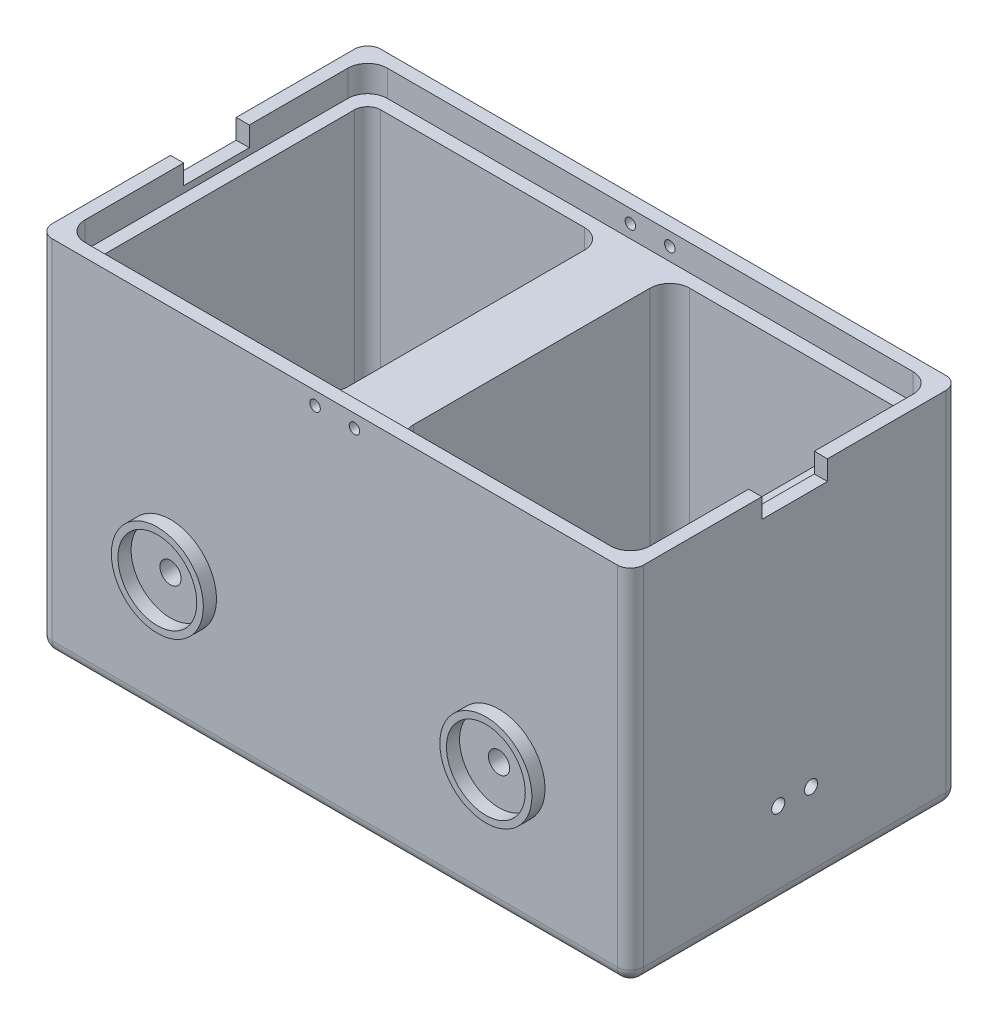
SolidWorks part; units mm, degrees
ref_plane "Front Plane" through (0, 0, 0) normal (0, 0, 1) x (1, 0, 0)
ref_plane "Top Plane" through (0, 0, 0) normal (0, 1, 0) x (1, 0, 0)
ref_plane "Right Plane" through (0, 0, 0) normal (1, 0, 0) x (0, 0, -1)
sketch "Sketch1" plane through (0, 0, 0) normal (0, 1, 0) x (1, 0, 0)
  line L0 (-78.5714, 0) -> (88.7218, 0) construction
  line L1 (-43, 25) -> (43, 25)
  line L2 (-45, 23) -> (-45, -23)
  line L3 (-43, -25) -> (43, -25)
  line L4 (45, 23) -> (45, -23)
  line L5 (0, 21) -> (0, -45.3008) construction
  line L6 (-5, 18) -> (-5, -18)
  line L7 (-39, 21) -> (-8, 21)
  line L8 (-41, 19) -> (-41, -19)
  line L9 (-39, -21) -> (-8, -21)
  line L10 (41, 19) -> (41, -18)
  line L12 (8, 21) -> (39, 21)
  line L13 (8, -21) -> (38, -21)
  line L14 (5, 18) -> (5, -18)
  arc A0 (38, -21) -> (41, -18) centre (38, -18) ccw
  arc A1 (-8, -21) -> (-5, -18) centre (-8, -18) ccw
  arc A2 (8, -21) -> (5, -18) centre (8, -18) cw
  arc A3 (8, 21) -> (5, 18) centre (8, 18) ccw
  arc A4 (-8, 21) -> (-5, 18) centre (-8, 18) cw
  arc A5 (-41, -19) -> (-39, -21) centre (-39, -19) ccw
  arc A6 (-39, 21) -> (-41, 19) centre (-39, 19) ccw
  arc A7 (39, 21) -> (41, 19) centre (39, 19) cw
  arc A8 (43, 25) -> (45, 23) centre (43, 23) cw
  arc A9 (43, -25) -> (45, -23) centre (43, -23) ccw
  arc A10 (-45, -23) -> (-43, -25) centre (-43, -23) ccw
  arc A11 (-43, 25) -> (-45, 23) centre (-43, 23) ccw
  point P21 (2, -21)
  point P24 (1, 21)
  point P37 (45, 25)
  point P40 (45, -25)
  point P45 (-45, 25)
  dimension "D6" = 3
  dimension "D7" = 3
  dimension "D1" = 50
  dimension "D2" = 90
  dimension "D3" = 4
  dimension "D4" = 4
  dimension "D5" = 10
  dimension "D8" = 90
extrude "Boss-Extrude1" add sketch "Sketch1" along normal blind 55
sketch "Sketch2" plane through (0, 0, 0) normal (0, -1, 0) x (1, 0, 0)
  line L0 (45, 23) -> (45, -23) construction
  line L1 (43, -25) -> (-43, -25) construction
  line L2 (-45, -23) -> (-45, 23) construction
  line L3 (-43, 25) -> (43, 25) construction
  line L4 (45, 23) -> (45, -23)
  line L5 (43, -25) -> (-43, -25)
  line L6 (-45, -23) -> (-45, 23)
  line L7 (-43, 25) -> (43, 25)
  arc A0 (-45, -23) -> (-43, -25) centre (-43, -23) ccw construction
  arc A1 (45, 23) -> (43, 25) centre (43, 23) ccw construction
  arc A2 (43, -25) -> (45, -23) centre (43, -23) ccw construction
  arc A3 (-43, 25) -> (-45, 23) centre (-43, 23) ccw construction
  arc A4 (-45, -23) -> (-43, -25) centre (-43, -23) ccw
  arc A5 (45, 23) -> (43, 25) centre (43, 23) ccw
  arc A6 (43, -25) -> (45, -23) centre (43, -23) ccw
  arc A7 (-43, 25) -> (-45, 23) centre (-43, 23) ccw
extrude "Boss-Extrude2" add sketch "Sketch2" against normal blind 4
sketch "Sketch5" plane through (0, 55, 0) normal (0, 1, 0) x (1, 0, 0)
  line L0 (43, 25) -> (-43, 25) construction
  line L1 (-40, 23) -> (40, 23)
  line L2 (-43, 20) -> (-43, -20)
  line L3 (-40, -23) -> (40, -23)
  line L4 (43, 20) -> (43, -20)
  line L5 (-43, -25) -> (43, -25) construction
  line L6 (41, -18) -> (41, 19) construction
  line L7 (-45, 23) -> (-45, -23) construction
  arc A0 (40, 23) -> (43, 20) centre (40, 20) cw
  arc A1 (40, -23) -> (43, -20) centre (40, -20) ccw
  arc A2 (-43, -20) -> (-40, -23) centre (-40, -20) ccw
  arc A3 (-40, 23) -> (-43, 20) centre (-40, 20) ccw
  dimension "D5" = 3
  dimension "D1" = 2
  dimension "D2" = 2
  dimension "D3" = 2
  dimension "D4" = 2
extrude "Cut-Extrude1" cut sketch "Sketch5" against normal blind 4
sketch "Sketch6" plane through (0, 0, 25) normal (0, 0, 1) x (1, 0, 0)
  line L0 (0, 65.631) -> (0, -11.3005) construction
  line L1 (-65.663, 20) -> (62.9075, 20) construction
  line L2 (-25, 33.8045) -> (-25, 8.3012) construction
  line L3 (25, 33.8045) -> (25, 8.3012) construction
  circle A0 centre (-25, 20) radius 7
  circle A1 centre (25, 20) radius 7
  dimension "D4" = 14
  dimension "D1" = 20
  dimension "D2" = 25
  dimension "D3" = 25
extrude "Boss-Extrude3" add sketch "Sketch6" along normal blind 2
sketch "Sketch7" plane through (0, 0, 27) normal (0, 0, 1) x (1, 0, 0)
  circle A0 centre (25, 20) radius 6
  dimension "D1" = 12
extrude "Cut-Extrude2" cut sketch "Sketch7" against normal blind 2
sketch "Sketch8" plane through (0, 0, 25) normal (0, 0, 1) x (1, 0, 0)
  circle A0 centre (25, 20) radius 1.6139
extrude "Cut-Extrude4" cut sketch "Sketch8" against normal blind 13
sketch "Sketch9" plane through (0, 0, 27) normal (0, 0, 1) x (1, 0, 0)
  circle A0 centre (-25, 20) radius 6
extrude "Cut-Extrude5" cut sketch "Sketch9" against normal blind 2
sketch "Sketch11" plane through (0, 0, 25) normal (0, 0, 1) x (1, 0, 0)
  circle A0 centre (-25, 20) radius 1.615
  dimension "D1" = 3.23
extrude "Cut-Extrude6" cut sketch "Sketch11" against normal blind 6
fillet "Fillet1" radius 2 8 edges at (0, 0, -25) (-44.4142, 0, -24.4142) (-45, 0, 0) (-44.4142, 0, 24.4142) (0, 0, 25) (44.4142, 0, 24.4142) (45, 0, 0) (44.4142, 0, -24.4142)
sketch "Sketch14" plane through (0, 0, -25) normal (0, 0, -1) x (-1, 0, 0)
  circle A0 centre (25, 20) radius 6 construction
  circle A1 centre (25, 20) radius 1.615 construction
  circle A2 centre (-25, 20) radius 1.6139 construction
  circle A3 centre (-25, 20) radius 6 construction
  circle A4 centre (-25, 20) radius 7 construction
  circle A5 centre (25, 20) radius 7 construction
  circle A6 centre (25, 20) radius 6
  circle A7 centre (25, 20) radius 1.615
  circle A8 centre (-25, 20) radius 1.6139
  circle A9 centre (-25, 20) radius 6
  circle A10 centre (-25, 20) radius 7
  circle A11 centre (25, 20) radius 7
extrude "Boss-Extrude5" add sketch "Sketch14" along normal blind 2 contours A10 A9 | A11 A6
sketch "Sketch15" plane through (0, 0, -25) normal (0, 0, -1) x (-1, 0, 0)
  circle A0 centre (25, 20) radius 1.615 construction
  circle A1 centre (-25, 20) radius 1.6139 construction
  circle A2 centre (25, 20) radius 1.615
  circle A3 centre (-25, 20) radius 1.6139
extrude "Cut-Extrude7" cut sketch "Sketch15" against normal blind 6
sketch "Sketch16" plane through (45, 0, 0) normal (1, 0, 0) x (0, 0, -1)
  line L0 (0, -3.0222) -> (0, 58.7431) construction
  line L1 (-27, 13) -> (41.0171, 13) construction
  line L2 (-27, 27) -> (-27, 13) construction
  circle A0 centre (-2.5, 13) radius 1
  circle A1 centre (2.5, 13) radius 1
  dimension "D1" = 2
  dimension "D2" = 2.5
extrude "Cut-Extrude9" cut sketch "Sketch16" against normal blind 6
sketch "Sketch17" plane through (-45, 0, 0) normal (-1, 0, 0) x (0, 0, 1)
  circle A0 centre (-2.5, 13) radius 1 construction
  circle A1 centre (2.5, 13) radius 1 construction
  circle A2 centre (-2.5, 13) radius 1
  circle A3 centre (2.5, 13) radius 1
extrude "Cut-Extrude10" cut sketch "Sketch17" against normal blind 6
sketch "Sketch18" plane through (0, 55, 0) normal (0, 1, 0) x (1, 0, 0)
  line L0 (58.9312, 0) -> (-54.3972, 0) construction
  line L1 (-54.3972, 5) -> (58.9312, 5) construction
  line L2 (-54.3972, -5) -> (58.9312, -5) construction
  line L3 (42.9031, 5) -> (45.007, 5)
  line L4 (45.007, 5) -> (45.007, -5)
  line L5 (45.007, -5) -> (42.9031, -5)
  line L6 (42.9031, -5) -> (42.9031, 5)
  line L7 (0, 46.5911) -> (0, -41.7781) construction
  line L8 (-45.007, -5) -> (-42.9031, -5)
  line L9 (-45.007, 5) -> (-45.007, -5)
  line L10 (-42.9031, -5) -> (-42.9031, 5)
  line L11 (-42.9031, 5) -> (-45.007, 5)
  dimension "D1" = 5
extrude "Cut-Extrude12" cut sketch "Sketch18" against normal blind 3
sketch "Sketch19" plane through (0, 0, 25) normal (0, 0, 1) x (1, 0, 0)
  line L0 (-53.5561, 51) -> (63.9219, 51) construction
  line L1 (-43, 55) -> (43, 55) construction
  line L2 (0, -5.55) -> (0, 65.1473) construction
  line L3 (-53.5561, 53) -> (78.7984, 53) construction
  circle A0 centre (-3, 53) radius 0.8
  circle A1 centre (3, 53) radius 0.8
  dimension "D3" = 1.6
  dimension "D1" = 4
  dimension "D2" = 2
  dimension "D4" = 3
extrude "Cut-Extrude13" cut sketch "Sketch19" against normal up to surface (50 mm away) up to face at (-18, 20, -25)
